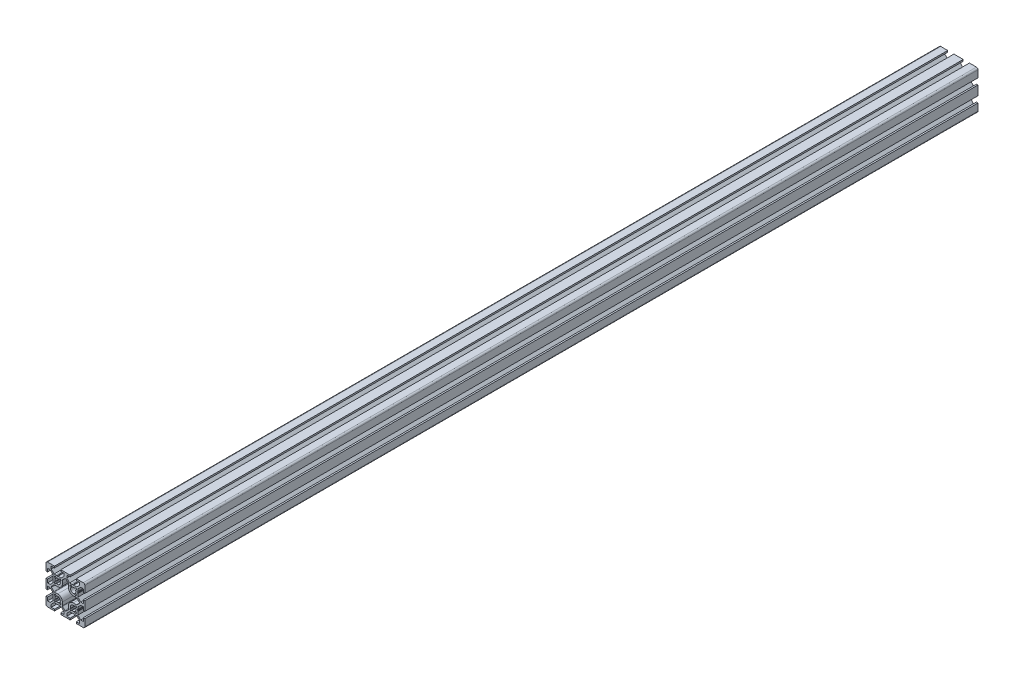
SolidWorks part; units mm, degrees
ref_plane "Front Plane" through (0, 0, 0) normal (0, 0, 1) x (1, 0, 0)
ref_plane "Top Plane" through (0, 0, 0) normal (0, 1, 0) x (1, 0, 0)
ref_plane "Right Plane" through (0, 0, 0) normal (1, 0, 0) x (0, 0, -1)
ref_plane "Plane1" through (0, 0, 0) normal (0, 0, 1) x (1, 0, 0)
sketch "Sketch1" plane through (0, 0, 0) normal (0, 0, 1) x (1, 0, 0)
  line L0 (-25, 23) -> (-25, 14)
  line L1 (-25, 14) -> (-23, 14)
  line L2 (-23, 14) -> (-23, 18.25)
  line L3 (-23, 18.25) -> (-19.6642, 18.25)
  line L4 (-19.6642, 18.25) -> (-16, 14.5858)
  line L5 (-16, 14.5858) -> (-16, 10.6536)
  line L6 (-15.933, 10.4036) -> (-15.7, 10)
  line L7 (-15.7, 10) -> (-15.933, 9.5964)
  line L8 (-15.933, 9.0964) -> (-15.751, 8.7811)
  line L9 (-15.751, 8.7811) -> (-16, 7.5)
  line L10 (-16, 7.5) -> (-16, 5.4142)
  line L11 (-16, 5.4142) -> (-19.6642, 1.75)
  line L12 (-19.6642, 1.75) -> (-23, 1.75)
  line L13 (-23, 1.75) -> (-23, 6)
  line L14 (-23, 6) -> (-25, 6)
  line L15 (-25, 6) -> (-25, -6)
  line L16 (-25, -6) -> (-23, -6)
  line L17 (-23, -6) -> (-23, -1.75)
  line L18 (-23, -1.75) -> (-19.6642, -1.75)
  line L19 (-19.6642, -1.75) -> (-16, -5.4142)
  line L20 (-16, -5.4142) -> (-16, -9.3464)
  line L21 (-15.933, -9.5964) -> (-15.7, -10)
  line L22 (-15.7, -10) -> (-15.933, -10.4036)
  line L23 (-15.933, -10.9036) -> (-15.751, -11.2189)
  line L24 (-15.751, -11.2189) -> (-16, -12.5)
  line L25 (-16, -12.5) -> (-16, -14.5858)
  line L26 (-16, -14.5858) -> (-19.6642, -18.25)
  line L27 (-19.6642, -18.25) -> (-23, -18.25)
  line L28 (-23, -18.25) -> (-23, -14)
  line L29 (-23, -14) -> (-25, -14)
  line L30 (-25, -14) -> (-25, -23)
  line L31 (-23, -25) -> (-14, -25)
  line L32 (-14, -25) -> (-14, -23)
  line L33 (-14, -23) -> (-18.25, -23)
  line L34 (-18.25, -23) -> (-18.25, -19.6642)
  line L35 (-18.25, -19.6642) -> (-14.5858, -16)
  line L36 (-14.5858, -16) -> (-10.6536, -16)
  line L37 (-10.4036, -15.933) -> (-10, -15.7)
  line L38 (-10, -15.7) -> (-9.5964, -15.933)
  line L39 (-9.0964, -15.933) -> (-8.7811, -15.751)
  line L40 (-8.7811, -15.751) -> (-7.5, -16)
  line L41 (-7.5, -16) -> (-5.4142, -16)
  line L42 (-5.4142, -16) -> (-1.75, -19.6642)
  line L43 (-1.75, -19.6642) -> (-1.75, -23)
  line L44 (-1.75, -23) -> (-6, -23)
  line L45 (-6, -23) -> (-6, -25)
  line L46 (-6, -25) -> (6, -25)
  line L47 (6, -25) -> (6, -23)
  line L48 (6, -23) -> (1.75, -23)
  line L49 (1.75, -23) -> (1.75, -19.6642)
  line L50 (1.75, -19.6642) -> (5.4142, -16)
  line L51 (5.4142, -16) -> (9.3464, -16)
  line L52 (9.5964, -15.933) -> (10, -15.7)
  line L53 (10, -15.7) -> (10.4036, -15.933)
  line L54 (10.9036, -15.933) -> (11.2189, -15.751)
  line L55 (11.2189, -15.751) -> (12.5, -16)
  line L56 (12.5, -16) -> (14.5858, -16)
  line L57 (14.5858, -16) -> (18.25, -19.6642)
  line L58 (18.25, -19.6642) -> (18.25, -23)
  line L59 (18.25, -23) -> (14, -23)
  line L60 (14, -23) -> (14, -25)
  line L61 (14, -25) -> (23, -25)
  line L62 (25, -23) -> (25, -14)
  line L63 (25, -14) -> (23, -14)
  line L64 (23, -14) -> (23, -18.25)
  line L65 (23, -18.25) -> (19.6642, -18.25)
  line L66 (19.6642, -18.25) -> (16, -14.5858)
  line L67 (16, -14.5858) -> (16, -10.6536)
  line L68 (15.933, -10.4036) -> (15.7, -10)
  line L69 (15.7, -10) -> (15.933, -9.5964)
  line L70 (15.933, -9.0964) -> (15.751, -8.7811)
  line L71 (15.751, -8.7811) -> (16, -7.5)
  line L72 (16, -7.5) -> (16, -5.4142)
  line L73 (16, -5.4142) -> (19.6642, -1.75)
  line L74 (19.6642, -1.75) -> (23, -1.75)
  line L75 (23, -1.75) -> (23, -6)
  line L76 (23, -6) -> (25, -6)
  line L77 (25, -6) -> (25, 6)
  line L78 (25, 6) -> (23, 6)
  line L79 (23, 6) -> (23, 1.75)
  line L80 (23, 1.75) -> (19.6642, 1.75)
  line L81 (19.6642, 1.75) -> (16, 5.4142)
  line L82 (16, 5.4142) -> (16, 9.3464)
  line L83 (15.933, 9.5964) -> (15.7, 10)
  line L84 (15.7, 10) -> (15.933, 10.4036)
  line L85 (15.933, 10.9036) -> (15.751, 11.2189)
  line L86 (15.751, 11.2189) -> (16, 12.5)
  line L87 (16, 12.5) -> (16, 14.5858)
  line L88 (16, 14.5858) -> (19.6642, 18.25)
  line L89 (19.6642, 18.25) -> (23, 18.25)
  line L90 (23, 18.25) -> (23, 14)
  line L91 (23, 14) -> (25, 14)
  line L92 (25, 14) -> (25, 23)
  line L93 (23, 25) -> (14, 25)
  line L94 (14, 25) -> (14, 23)
  line L95 (14, 23) -> (18.25, 23)
  line L96 (18.25, 23) -> (18.25, 19.6642)
  line L97 (18.25, 19.6642) -> (14.5858, 16)
  line L98 (14.5858, 16) -> (10.6536, 16)
  line L99 (10.4036, 15.933) -> (10, 15.7)
  line L100 (10, 15.7) -> (9.5964, 15.933)
  line L101 (9.0964, 15.933) -> (8.7811, 15.751)
  line L102 (8.7811, 15.751) -> (7.5, 16)
  line L103 (7.5, 16) -> (5.4142, 16)
  line L104 (5.4142, 16) -> (1.75, 19.6642)
  line L105 (1.75, 19.6642) -> (1.75, 23)
  line L106 (1.75, 23) -> (6, 23)
  line L107 (6, 23) -> (6, 25)
  line L108 (6, 25) -> (-6, 25)
  line L109 (-6, 25) -> (-6, 23)
  line L110 (-6, 23) -> (-1.75, 23)
  line L111 (-1.75, 23) -> (-1.75, 19.6642)
  line L112 (-1.75, 19.6642) -> (-5.4142, 16)
  line L113 (-5.4142, 16) -> (-9.3464, 16)
  line L114 (-9.5964, 15.933) -> (-10, 15.7)
  line L115 (-10, 15.7) -> (-10.4036, 15.933)
  line L116 (-10.9036, 15.933) -> (-11.2189, 15.751)
  line L117 (-11.2189, 15.751) -> (-12.5, 16)
  line L118 (-12.5, 16) -> (-14.5858, 16)
  line L119 (-14.5858, 16) -> (-18.25, 19.6642)
  line L120 (-18.25, 19.6642) -> (-18.25, 23)
  line L121 (-18.25, 23) -> (-14, 23)
  line L122 (-14, 23) -> (-14, 25)
  line L123 (-14, 25) -> (-23, 25)
  line L124 (-17.8787, -0.7071) -> (-14.8787, -3.7071)
  line L125 (-14.1716, -4) -> (-10, -4)
  line L126 (-4, -10) -> (-4, -14.1716)
  line L127 (-3.7071, -14.8787) -> (-0.7071, -17.8787)
  line L128 (0.7071, -17.8787) -> (3.7071, -14.8787)
  line L129 (4, -14.1716) -> (4, -10)
  line L130 (10, -4) -> (14.1716, -4)
  line L131 (14.8787, -3.7071) -> (17.8787, -0.7071)
  line L132 (17.8787, 0.7071) -> (14.8787, 3.7071)
  line L133 (14.1716, 4) -> (10, 4)
  line L134 (4, 10) -> (4, 14.1716)
  line L135 (3.7071, 14.8787) -> (0.7071, 17.8787)
  line L136 (-0.7071, 17.8787) -> (-3.7071, 14.8787)
  line L137 (-4, 14.1716) -> (-4, 10)
  line L138 (-10, 4) -> (-14.1716, 4)
  line L139 (-14.8787, 3.7071) -> (-17.8787, 0.7071)
  arc A0 (-16, 10.6536) -> (-15.933, 10.4036) centre (-15.5, 10.6536) ccw
  arc A1 (-15.933, 9.5964) -> (-15.933, 9.0964) centre (-15.5, 9.3464) ccw
  arc A2 (-16, -9.3464) -> (-15.933, -9.5964) centre (-15.5, -9.3464) ccw
  arc A3 (-15.933, -10.4036) -> (-15.933, -10.9036) centre (-15.5, -10.6536) ccw
  arc A4 (-25, -23) -> (-23, -25) centre (-23, -23) ccw
  arc A5 (-10.6536, -16) -> (-10.4036, -15.933) centre (-10.6536, -15.5) ccw
  arc A6 (-9.5964, -15.933) -> (-9.0964, -15.933) centre (-9.3464, -15.5) ccw
  arc A7 (9.3464, -16) -> (9.5964, -15.933) centre (9.3464, -15.5) ccw
  arc A8 (10.4036, -15.933) -> (10.9036, -15.933) centre (10.6536, -15.5) ccw
  arc A9 (23, -25) -> (25, -23) centre (23, -23) ccw
  arc A10 (16, -10.6536) -> (15.933, -10.4036) centre (15.5, -10.6536) ccw
  arc A11 (15.933, -9.5964) -> (15.933, -9.0964) centre (15.5, -9.3464) ccw
  arc A12 (16, 9.3464) -> (15.933, 9.5964) centre (15.5, 9.3464) ccw
  arc A13 (15.933, 10.4036) -> (15.933, 10.9036) centre (15.5, 10.6536) ccw
  arc A14 (25, 23) -> (23, 25) centre (23, 23) ccw
  arc A15 (10.6536, 16) -> (10.4036, 15.933) centre (10.6536, 15.5) ccw
  arc A16 (9.5964, 15.933) -> (9.0964, 15.933) centre (9.3464, 15.5) ccw
  arc A17 (-9.3464, 16) -> (-9.5964, 15.933) centre (-9.3464, 15.5) ccw
  arc A18 (-10.4036, 15.933) -> (-10.9036, 15.933) centre (-10.6536, 15.5) ccw
  arc A19 (-23, 25) -> (-25, 23) centre (-23, 23) ccw
  arc A20 (-17.8787, 0.7071) -> (-17.8787, -0.7071) centre (-17.1716, 0) ccw
  arc A21 (-14.8787, -3.7071) -> (-14.1716, -4) centre (-14.1716, -3) ccw
  arc A22 (-10, -4) -> (-4, -10) centre (-10, -10) cw
  arc A23 (-4, -14.1716) -> (-3.7071, -14.8787) centre (-3, -14.1716) ccw
  arc A24 (-0.7071, -17.8787) -> (0.7071, -17.8787) centre (0, -17.1716) ccw
  arc A25 (3.7071, -14.8787) -> (4, -14.1716) centre (3, -14.1716) ccw
  arc A26 (4, -10) -> (10, -4) centre (10, -10) cw
  arc A27 (14.1716, -4) -> (14.8787, -3.7071) centre (14.1716, -3) ccw
  arc A28 (17.8787, -0.7071) -> (17.8787, 0.7071) centre (17.1716, 0) ccw
  arc A29 (14.8787, 3.7071) -> (14.1716, 4) centre (14.1716, 3) ccw
  arc A30 (10, 4) -> (4, 10) centre (10, 10) cw
  arc A31 (4, 14.1716) -> (3.7071, 14.8787) centre (3, 14.1716) ccw
  arc A32 (0.7071, 17.8787) -> (-0.7071, 17.8787) centre (0, 17.1716) ccw
  arc A33 (-3.7071, 14.8787) -> (-4, 14.1716) centre (-3, 14.1716) ccw
  arc A34 (-4, 10) -> (-10, 4) centre (-10, 10) cw
  arc A35 (-14.1716, 4) -> (-14.8787, 3.7071) centre (-14.1716, 3) ccw
extrude "Boss-Extrude1" add sketch "Sketch1" against normal blind 1150
ref_plane "Plane2" through (0, 0, 0) normal (0, 0, 1) x (1, 0, 0)
sketch "Sketch2" plane through (0, 0, 0) normal (0, 0, 1) x (1, 0, 0)
  line L0 (-14.2426, 12.8284) -> (-13.2051, 11.7909)
  line L1 (-13.2051, 8.2091) -> (-14.2426, 7.1716)
  line L2 (-14.2426, 6.4645) -> (-13.5355, 5.7574)
  line L3 (-12.8284, 5.7574) -> (-11.7909, 6.7949)
  line L4 (-6.7949, 11.7909) -> (-5.7574, 12.8284)
  line L5 (-5.7574, 13.5355) -> (-6.4645, 14.2426)
  line L6 (-7.1716, 14.2426) -> (-8.2091, 13.2051)
  line L7 (-11.7909, 13.2051) -> (-12.8284, 14.2426)
  line L8 (-13.5355, 14.2426) -> (-14.2426, 13.5355)
  arc A0 (-14.2426, 13.5355) -> (-14.2426, 12.8284) centre (-13.8891, 13.182) ccw
  arc A1 (-13.2051, 11.7909) -> (-13.1208, 11.3493) centre (-13.4879, 11.508) cw
  arc A2 (-13.1208, 11.3493) -> (-13.1208, 8.6507) centre (-10, 10) ccw
  arc A3 (-13.1208, 8.6507) -> (-13.2051, 8.2091) centre (-13.4879, 8.492) cw
  arc A4 (-14.2426, 7.1716) -> (-14.2426, 6.4645) centre (-13.8891, 6.818) ccw
  arc A5 (-13.5355, 5.7574) -> (-12.8284, 5.7574) centre (-13.182, 6.1109) ccw
  arc A6 (-11.7909, 6.7949) -> (-11.3493, 6.8792) centre (-11.508, 6.5121) cw
  arc A7 (-11.3493, 6.8792) -> (-6.8792, 11.3493) centre (-10, 10) ccw
  arc A8 (-6.8792, 11.3493) -> (-6.7949, 11.7909) centre (-6.5121, 11.508) cw
  arc A9 (-5.7574, 12.8284) -> (-5.7574, 13.5355) centre (-6.1109, 13.182) ccw
  arc A10 (-6.4645, 14.2426) -> (-7.1716, 14.2426) centre (-6.818, 13.8891) ccw
  arc A11 (-8.2091, 13.2051) -> (-8.6507, 13.1208) centre (-8.492, 13.4879) cw
  arc A12 (-8.6507, 13.1208) -> (-11.3493, 13.1208) centre (-10, 10) ccw
  arc A13 (-11.3493, 13.1208) -> (-11.7909, 13.2051) centre (-11.508, 13.4879) cw
  arc A14 (-12.8284, 14.2426) -> (-13.5355, 14.2426) centre (-13.182, 13.8891) ccw
extrude "Cut-Extrude1" cut sketch "Sketch2" against normal through all
ref_plane "Plane3" through (0, 0, 0) normal (0, 0, 1) x (1, 0, 0)
sketch "Sketch3" plane through (0, 0, 0) normal (0, 0, 1) x (1, 0, 0)
  line L0 (-12.8284, -14.2426) -> (-11.7909, -13.2051)
  line L1 (-8.2091, -13.2051) -> (-7.1716, -14.2426)
  line L2 (-6.4645, -14.2426) -> (-5.7574, -13.5355)
  line L3 (-5.7574, -12.8284) -> (-6.7949, -11.7909)
  line L4 (-11.7909, -6.7949) -> (-12.8284, -5.7574)
  line L5 (-13.5355, -5.7574) -> (-14.2426, -6.4645)
  line L6 (-14.2426, -7.1716) -> (-13.2051, -8.2091)
  line L7 (-13.2051, -11.7909) -> (-14.2426, -12.8284)
  line L8 (-14.2426, -13.5355) -> (-13.5355, -14.2426)
  arc A0 (-13.5355, -14.2426) -> (-12.8284, -14.2426) centre (-13.182, -13.8891) ccw
  arc A1 (-11.7909, -13.2051) -> (-11.3493, -13.1208) centre (-11.508, -13.4879) cw
  arc A2 (-11.3493, -13.1208) -> (-8.6507, -13.1208) centre (-10, -10) ccw
  arc A3 (-8.6507, -13.1208) -> (-8.2091, -13.2051) centre (-8.492, -13.4879) cw
  arc A4 (-7.1716, -14.2426) -> (-6.4645, -14.2426) centre (-6.818, -13.8891) ccw
  arc A5 (-5.7574, -13.5355) -> (-5.7574, -12.8284) centre (-6.1109, -13.182) ccw
  arc A6 (-6.7949, -11.7909) -> (-6.8792, -11.3493) centre (-6.5121, -11.508) cw
  arc A7 (-6.8792, -11.3493) -> (-11.3493, -6.8792) centre (-10, -10) ccw
  arc A8 (-11.3493, -6.8792) -> (-11.7909, -6.7949) centre (-11.508, -6.5121) cw
  arc A9 (-12.8284, -5.7574) -> (-13.5355, -5.7574) centre (-13.182, -6.1109) ccw
  arc A10 (-14.2426, -6.4645) -> (-14.2426, -7.1716) centre (-13.8891, -6.818) ccw
  arc A11 (-13.2051, -8.2091) -> (-13.1208, -8.6507) centre (-13.4879, -8.492) cw
  arc A12 (-13.1208, -8.6507) -> (-13.1208, -11.3493) centre (-10, -10) ccw
  arc A13 (-13.1208, -11.3493) -> (-13.2051, -11.7909) centre (-13.4879, -11.508) cw
  arc A14 (-14.2426, -12.8284) -> (-14.2426, -13.5355) centre (-13.8891, -13.182) ccw
extrude "Cut-Extrude2" cut sketch "Sketch3" against normal through all
ref_plane "Plane4" through (0, 0, 0) normal (0, 0, 1) x (1, 0, 0)
sketch "Sketch4" plane through (0, 0, 0) normal (0, 0, 1) x (1, 0, 0)
  line L0 (14.2426, -12.8284) -> (13.2051, -11.7909)
  line L1 (13.2051, -8.2091) -> (14.2426, -7.1716)
  line L2 (14.2426, -6.4645) -> (13.5355, -5.7574)
  line L3 (12.8284, -5.7574) -> (11.7909, -6.7949)
  line L4 (6.7949, -11.7909) -> (5.7574, -12.8284)
  line L5 (5.7574, -13.5355) -> (6.4645, -14.2426)
  line L6 (7.1716, -14.2426) -> (8.2091, -13.2051)
  line L7 (11.7909, -13.2051) -> (12.8284, -14.2426)
  line L8 (13.5355, -14.2426) -> (14.2426, -13.5355)
  arc A0 (14.2426, -13.5355) -> (14.2426, -12.8284) centre (13.8891, -13.182) ccw
  arc A1 (13.2051, -11.7909) -> (13.1208, -11.3493) centre (13.4879, -11.508) cw
  arc A2 (13.1208, -11.3493) -> (13.1208, -8.6507) centre (10, -10) ccw
  arc A3 (13.1208, -8.6507) -> (13.2051, -8.2091) centre (13.4879, -8.492) cw
  arc A4 (14.2426, -7.1716) -> (14.2426, -6.4645) centre (13.8891, -6.818) ccw
  arc A5 (13.5355, -5.7574) -> (12.8284, -5.7574) centre (13.182, -6.1109) ccw
  arc A6 (11.7909, -6.7949) -> (11.3493, -6.8792) centre (11.508, -6.5121) cw
  arc A7 (11.3493, -6.8792) -> (6.8792, -11.3493) centre (10, -10) ccw
  arc A8 (6.8792, -11.3493) -> (6.7949, -11.7909) centre (6.5121, -11.508) cw
  arc A9 (5.7574, -12.8284) -> (5.7574, -13.5355) centre (6.1109, -13.182) ccw
  arc A10 (6.4645, -14.2426) -> (7.1716, -14.2426) centre (6.818, -13.8891) ccw
  arc A11 (8.2091, -13.2051) -> (8.6507, -13.1208) centre (8.492, -13.4879) cw
  arc A12 (8.6507, -13.1208) -> (11.3493, -13.1208) centre (10, -10) ccw
  arc A13 (11.3493, -13.1208) -> (11.7909, -13.2051) centre (11.508, -13.4879) cw
  arc A14 (12.8284, -14.2426) -> (13.5355, -14.2426) centre (13.182, -13.8891) ccw
extrude "Cut-Extrude3" cut sketch "Sketch4" against normal through all
ref_plane "Plane5" through (0, 0, 0) normal (0, 0, 1) x (1, 0, 0)
sketch "Sketch5" plane through (0, 0, 0) normal (0, 0, 1) x (1, 0, 0)
  line L0 (12.8284, 14.2426) -> (11.7909, 13.2051)
  line L1 (8.2091, 13.2051) -> (7.1716, 14.2426)
  line L2 (6.4645, 14.2426) -> (5.7574, 13.5355)
  line L3 (5.7574, 12.8284) -> (6.7949, 11.7909)
  line L4 (11.7909, 6.7949) -> (12.8284, 5.7574)
  line L5 (13.5355, 5.7574) -> (14.2426, 6.4645)
  line L6 (14.2426, 7.1716) -> (13.2051, 8.2091)
  line L7 (13.2051, 11.7909) -> (14.2426, 12.8284)
  line L8 (14.2426, 13.5355) -> (13.5355, 14.2426)
  arc A0 (13.5355, 14.2426) -> (12.8284, 14.2426) centre (13.182, 13.8891) ccw
  arc A1 (11.7909, 13.2051) -> (11.3493, 13.1208) centre (11.508, 13.4879) cw
  arc A2 (11.3493, 13.1208) -> (8.6507, 13.1208) centre (10, 10) ccw
  arc A3 (8.6507, 13.1208) -> (8.2091, 13.2051) centre (8.492, 13.4879) cw
  arc A4 (7.1716, 14.2426) -> (6.4645, 14.2426) centre (6.818, 13.8891) ccw
  arc A5 (5.7574, 13.5355) -> (5.7574, 12.8284) centre (6.1109, 13.182) ccw
  arc A6 (6.7949, 11.7909) -> (6.8792, 11.3493) centre (6.5121, 11.508) cw
  arc A7 (6.8792, 11.3493) -> (11.3493, 6.8792) centre (10, 10) ccw
  arc A8 (11.3493, 6.8792) -> (11.7909, 6.7949) centre (11.508, 6.5121) cw
  arc A9 (12.8284, 5.7574) -> (13.5355, 5.7574) centre (13.182, 6.1109) ccw
  arc A10 (14.2426, 6.4645) -> (14.2426, 7.1716) centre (13.8891, 6.818) ccw
  arc A11 (13.2051, 8.2091) -> (13.1208, 8.6507) centre (13.4879, 8.492) cw
  arc A12 (13.1208, 8.6507) -> (13.1208, 11.3493) centre (10, 10) ccw
  arc A13 (13.1208, 11.3493) -> (13.2051, 11.7909) centre (13.4879, 11.508) cw
  arc A14 (14.2426, 12.8284) -> (14.2426, 13.5355) centre (13.8891, 13.182) ccw
extrude "Cut-Extrude4" cut sketch "Sketch5" against normal through all
